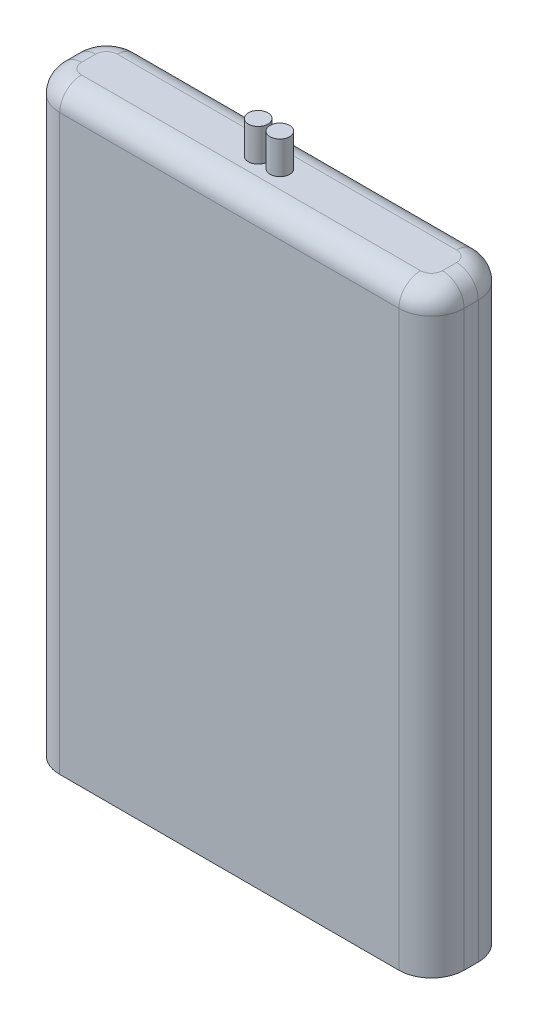
SolidWorks part; units mm, degrees
ref_plane "Front Plane" through (0, 0, 0) normal (0, 0, 1) x (1, 0, 0)
ref_plane "Top Plane" through (0, 0, 0) normal (0, 1, 0) x (1, 0, 0)
ref_plane "Right Plane" through (0, 0, 0) normal (1, 0, 0) x (0, 0, -1)
sketch "Sketch1" plane through (0, 0, 0) normal (0, 0, 1) x (1, 0, 0)
  line L1 (-18.58, 27.335) -> (18.58, 27.335)
  line L2 (-18.58, 27.335) -> (-18.58, -27.335)
  line L3 (-18.58, -27.335) -> (18.58, -27.335)
  line L4 (18.58, 27.335) -> (18.58, -27.335)
  line L5 (-18.58, 27.335) -> (18.58, -27.335) construction
  line L6 (-18.58, -27.335) -> (18.58, 27.335) construction
  point P0 (0, 0)
  dimension "D1" = 37.16
  dimension "D2" = 54.67
extrude "Boss-Extrude1" add sketch "Sketch1" along normal mid plane 7.3
fillet "Fillet1" radius 3 4 edges at (-18.58, 0, -3.65) (-18.58, 0, 3.65) (18.58, 0, -3.65) (18.58, 0, 3.65)
fillet "Fillet2" radius 2 8 edges at (17.7013, 27.335, 2.7713) (18.58, 27.335, 0) (17.7013, 27.335, -2.7713) (0, 27.335, -3.65) (-17.7013, 27.335, -2.7713) (-18.58, 27.335, 0) (-17.7013, 27.335, 2.7713) (0, 27.335, 3.65)
sketch "Sketch2" plane through (0, 27.335, 0) normal (0, 1, 0) x (1, 0, 0)
  line L0 (0, -10.285) -> (0, 21.7139) construction
  circle A0 centre (-1, 0) radius 0.9003
  circle A1 centre (1, 0) radius 0.9003
  dimension "D1" = 1.8007
  dimension "D2" = 1
extrude "Boss-Extrude2" add sketch "Sketch2" along normal blind 3
